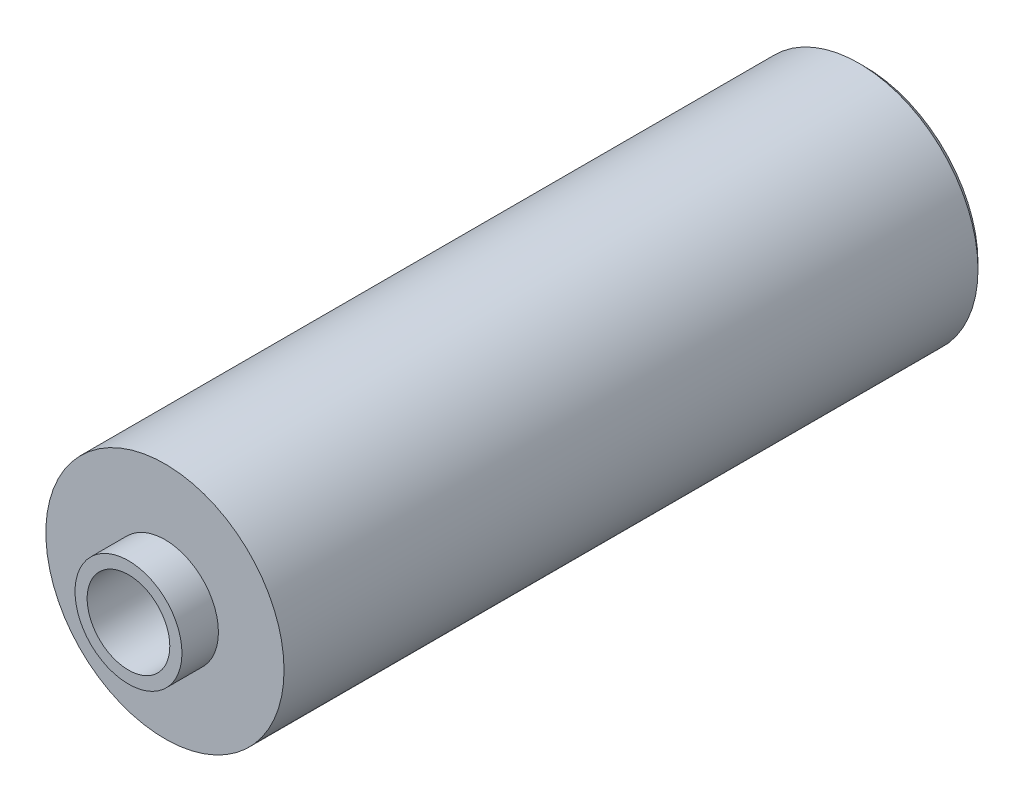
SolidWorks part; units mm, degrees
ref_plane "Front Plane" through (0, 0, 0) normal (0, 0, 1) x (1, 0, 0)
ref_plane "Top Plane" through (0, 0, 0) normal (0, 1, 0) x (1, 0, 0)
ref_plane "Right Plane" through (0, 0, 0) normal (1, 0, 0) x (0, 0, -1)
sketch "Sketch1" plane through (0, 0, 0) normal (0, 0, 1) x (1, 0, 0)
  circle A0 centre (0, 0) radius 1.7
  circle A2 centre (0, 0) radius 4.9
  dimension "D1" = 3.4
  dimension "D2" = 9.8
extrude "Boss-Extrude1" add sketch "Sketch1" along normal blind 28.8
sketch "Sketch2" plane through (0, 0, 28.8) normal (0, 0, 1) x (1, 0, 0)
  circle A0 centre (0, 0) radius 1.7
  circle A2 centre (0, 0) radius 2.2
  dimension "D1" = 3.4
  dimension "D2" = 0.5
extrude "Boss-Extrude2" add sketch "Sketch2" along normal blind 1.5
sketch "Sketch3" plane through (0, 0, 0) normal (0, 0, 1) x (1, 0, 0)
  circle A0 centre (0, 0) radius 2.2
  circle A1 centre (0, 0) radius 1.7
  dimension "D1" = 4.4
  dimension "D2" = 3.4
chamfer "Chamfer1" distance 0.25 angle 45 2 edges at (1.7, 0, 0) (4.9, 0, 0)
